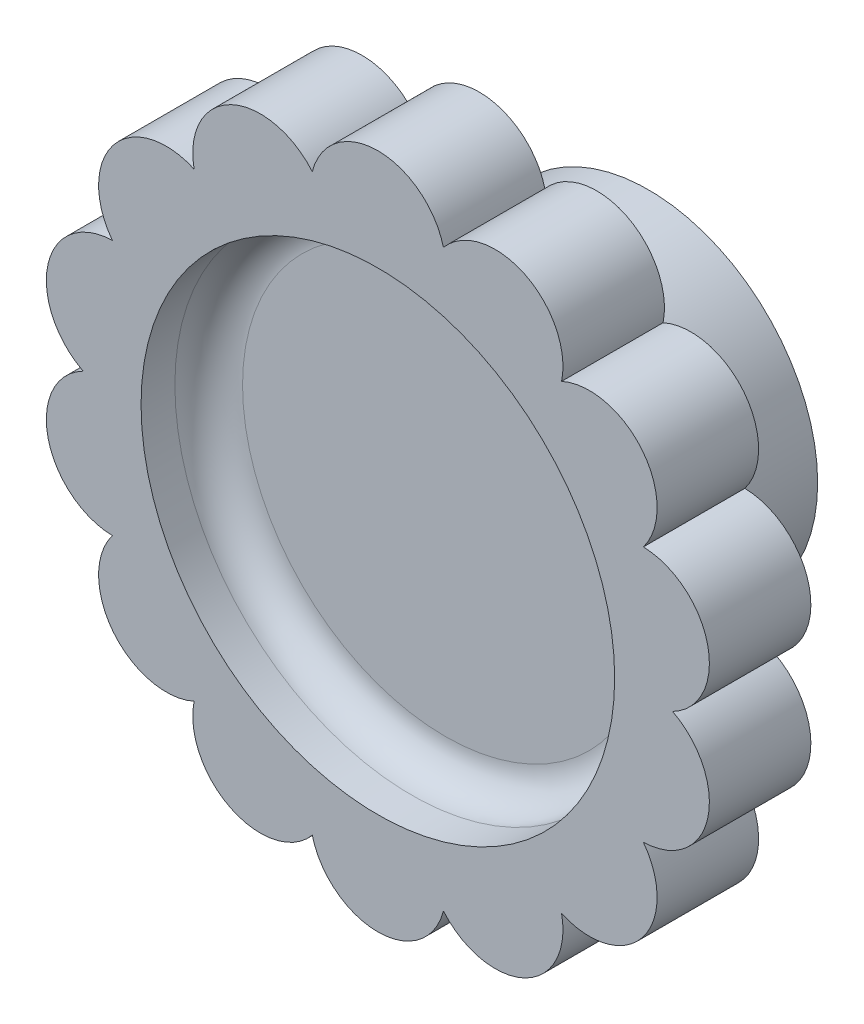
SolidWorks part; units mm, degrees
ref_plane "Спереди" through (0, 0, 0) normal (0, 0, 1) x (1, 0, 0)
ref_plane "Сверху" through (0, 0, 0) normal (0, 1, 0) x (1, 0, 0)
ref_plane "Справа" through (0, 0, 0) normal (1, 0, 0) x (0, 0, -1)
sketch "Эскиз1" plane through (0, 0, 0) normal (0, 0, 1) x (1, 0, 0)
  circle A0 centre (0, 0) radius 8
  circle A1 centre (0, 0) radius 10
extrude "Бобышка-Вытянуть1" add sketch "Эскиз1" along normal blind 10
sketch "Эскиз2" plane through (0, 0, 10) normal (0, 0, 1) x (1, 0, 0)
  arc A1 (3.8768, 16.9852) -> (-3.8768, 16.9852) centre (0, 16) ccw
  arc A2 (10.8625, 13.6211) -> (3.8768, 16.9852) centre (6.9421, 14.4155) ccw
  arc A3 (15.6967, 7.5591) -> (10.8625, 13.6211) centre (12.5093, 9.9758) ccw
  arc A4 (17.422, 0) -> (15.6967, 7.5591) centre (15.5988, 3.5603) ccw
  arc A5 (15.6967, -7.5591) -> (17.422, 0) centre (15.5988, -3.5603) ccw
  arc A6 (10.8625, -13.6211) -> (15.6967, -7.5591) centre (12.5093, -9.9758) ccw
  arc A7 (3.8768, -16.9852) -> (10.8625, -13.6211) centre (6.9421, -14.4155) ccw
  arc A8 (-3.8768, -16.9852) -> (3.8768, -16.9852) centre (0, -16) ccw
  arc A9 (-10.8625, -13.6211) -> (-3.8768, -16.9852) centre (-6.9421, -14.4155) ccw
  arc A10 (-15.6967, -7.5591) -> (-10.8625, -13.6211) centre (-12.5093, -9.9758) ccw
  arc A11 (-17.422, 0) -> (-15.6967, -7.5591) centre (-15.5988, -3.5603) ccw
  arc A12 (-15.6967, 7.5591) -> (-17.422, 0) centre (-15.5988, 3.5603) ccw
  arc A13 (-10.8625, 13.6211) -> (-15.6967, 7.5591) centre (-12.5093, 9.9758) ccw
  arc A14 (-3.8768, 16.9852) -> (-10.8625, 13.6211) centre (-6.9421, 14.4155) ccw
  point P42 (0, 0)
  dimension "D1" = 14
extrude "Бобышка-Вытянуть2" add sketch "Эскиз2" along normal blind 6
sketch "Эскиз3" plane through (0, 0, 16) normal (0, 0, 1) x (1, 0, 0)
  circle A0 centre (0, 0) radius 14
extrude "Вырез-Вытянуть1" cut sketch "Эскиз3" against normal blind 4
fillet "Скругление1" radius 2 1 edges at (14, 0, 12)
